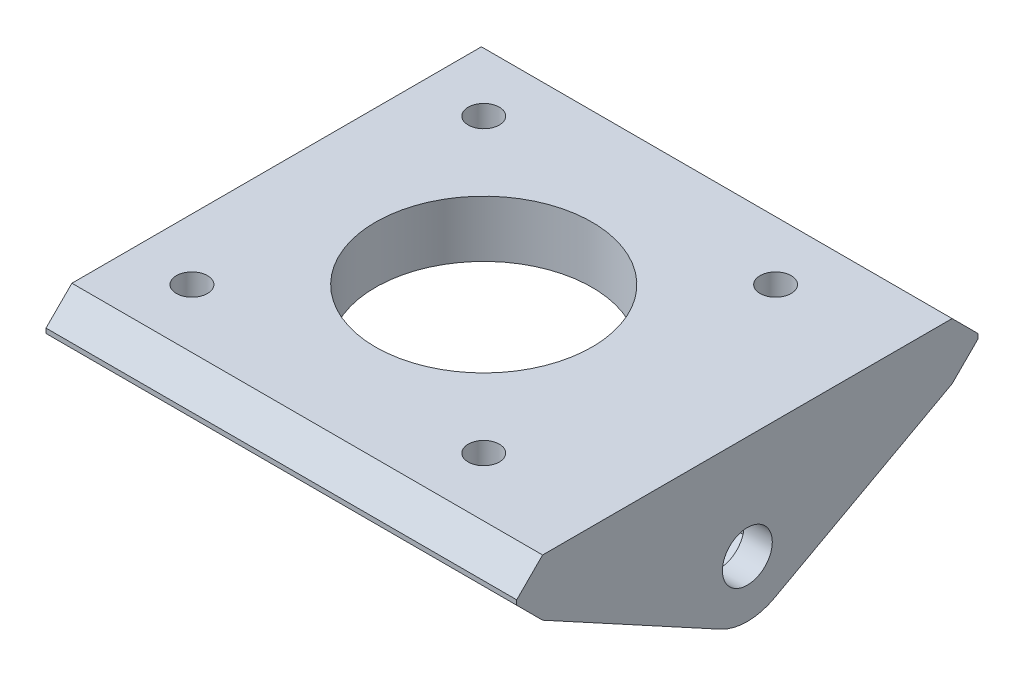
SolidWorks part; units mm, degrees
ref_plane "Front Plane" through (0, 0, 0) normal (0, 0, 1) x (1, 0, 0)
ref_plane "Top Plane" through (0, 0, 0) normal (0, 1, 0) x (1, 0, 0)
ref_plane "Right Plane" through (0, 0, 0) normal (1, 0, 0) x (0, 0, -1)
sketch "Sketch1" plane through (0, 0, 0) normal (0, 1, 0) x (1, 0, 0)
  line L1 (-22, -24.5) -> (22, -24.5)
  line L2 (-22, -24.5) -> (-22, 24.5)
  line L3 (-22, 24.5) -> (22, 24.5)
  line L4 (22, -24.5) -> (22, 24.5)
  line L5 (-22, -24.5) -> (22, 24.5) construction
  line L6 (-22, 24.5) -> (22, -24.5) construction
  line L11 (-15.5, -15.5) -> (15.5, 15.5) construction
  line L12 (-15.5, 15.5) -> (15.5, -15.5) construction
  line L13 (-15.5, 15.5) -> (15.5, 15.5) construction
  line L14 (-15.5, 15.5) -> (-15.5, -15.5) construction
  line L15 (-15.5, -15.5) -> (15.5, -15.5) construction
  line L16 (15.5, 15.5) -> (15.5, -15.5) construction
  line L17 (-15.5, 15.5) -> (15.5, -15.5) construction
  line L18 (-15.5, -15.5) -> (15.5, 15.5) construction
  circle A0 centre (0, 0) radius 11.5
  circle A1 centre (15.5, 15.5) radius 1.65
  circle A2 centre (15.5, -15.5) radius 1.65
  circle A3 centre (-15.5, -15.5) radius 1.65
  circle A4 centre (-15.5, 15.5) radius 1.65
  point P0 (0, 0)
  point P8 (-15.414, -15.414)
  point P10 (0, 0)
  point P11 (0, 0)
  point P13 (0, 0)
  point P15 (0, 0)
  point P19 (0, 0)
  point P20 (14.9848, 14.8863)
  dimension "D2" = 23
  dimension "D3" = 31
  dimension "D4" = 3.3
  dimension "D1" = 44
  dimension "D6" = 49
extrude "Boss-Extrude1" add sketch "Sketch1" along normal blind 6
chamfer "Chamfer1" distance 2.75 angle 45 8 edges at (22, 0, 0) (22, 6, 0) (-22, 0, 0) (-22, 6, 0) (0, 0, -24.5) (0, 6, -24.5) (0, 6, 24.5) (0, 0, 24.5)
sketch "Sketch2" plane through (22, 0, 0) normal (1, 0, 0) x (0, 0, -1)
  line L0 (0, -5) -> (0, 0) construction
  line L1 (-21.75, 6) -> (21.75, 6)
  line L2 (-21.75, 6) -> (-21.75, 0)
  line L4 (21.75, 6) -> (21.75, 0)
  line L5 (0, -9.9075) -> (4.25, -7.4537)
  line L6 (4.25, -7.4537) -> (4.25, -2.5463)
  line L7 (4.25, -2.5463) -> (0, -0.0925)
  line L8 (0, -0.0925) -> (-4.25, -2.5463)
  line L9 (-4.25, -2.5463) -> (-4.25, -7.4537)
  line L10 (-4.25, -7.4537) -> (0, -9.9075)
  line L11 (21.75, 0) -> (2.8668, -10.2708)
  line L12 (-21.75, 0) -> (-2.8668, -10.2708)
  circle A0 centre (0, -5) radius 4.25 construction
  arc A1 (-2.8668, -10.2708) -> (2.8668, -10.2708) centre (0, -5) ccw
  dimension "D3" = 6
  dimension "D1" = 8.5
  dimension "D2" = 5
extrude "Boss-Extrude2" add sketch "Sketch2" along normal blind 3
sketch "Sketch3" plane through (25, 0, 0) normal (1, 0, 0) x (0, 0, -1)
  line L0 (-21.75, 6) -> (21.75, 6)
  line L1 (21.75, 6) -> (21.75, 0)
  line L2 (21.75, 0) -> (2.8668, -10.2708)
  line L3 (-21.75, 0) -> (-2.8668, -10.2708)
  arc A0 (-2.8668, -10.2708) -> (2.8668, -10.2708) centre (0, -5) ccw
  circle A1 centre (0, -5) radius 2.65
  line M6 (-21.75, 6) -> (-21.75, 0)
  line M7 (-21.75, 0) -> (-2.8668, -10.2708)
  arc M8 (-2.8668, -10.2708) -> (2.8668, -10.2708) centre (0, -5) ccw
  line M9 (2.8668, -10.2708) -> (21.75, 0)
  line M10 (21.75, 0) -> (21.75, 6)
  line M11 (21.75, 6) -> (-21.75, 6)
  line M12 (4.25, -7.4537) -> (0, -9.9075)
  line M13 (0, -9.9075) -> (-4.25, -7.4537)
  line M14 (-4.25, -7.4537) -> (-4.25, -2.5463)
  line M15 (-4.25, -2.5463) -> (0, -0.0925)
  line M16 (0, -0.0925) -> (4.25, -2.5463)
  line M17 (4.25, -2.5463) -> (4.25, -7.4537)
  dimension "D1" = 5.3
extrude "Boss-Extrude3" add sketch "Sketch3" along normal blind 3 contours M11 M6 M7 M8 M9 M10 M17 M12 M13 M14 M15 M16 | A1 M12 M17 M16 M15 M14 M13
sketch "Sketch4" plane through (22, 0, 0) normal (1, 0, 0) x (0, 0, -1)
  line L4 (-21.75, 0) -> (-21.75, 6)
  line L5 (-21.75, 6) -> (-24.5, 3.25)
  line L6 (-24.5, 3.25) -> (-24.5, 2.75)
  line L7 (-24.5, 2.75) -> (-21.75, 0)
  line L8 (-21.75, 0) -> (-21.75, 6)
  line L9 (-21.75, 6) -> (-24.5, 3.25)
  line L10 (-24.5, 3.25) -> (-24.5, 2.75)
  line L11 (-24.5, 2.75) -> (-21.75, 0)
  line L12 (21.75, 6) -> (21.75, 0)
  line L13 (21.75, 0) -> (24.5, 2.75)
  line L14 (24.5, 2.75) -> (24.5, 3.25)
  line L15 (24.5, 3.25) -> (21.75, 6)
  line L16 (21.75, 6) -> (21.75, 0)
  line L17 (21.75, 0) -> (24.5, 2.75)
  line L18 (24.5, 2.75) -> (24.5, 3.25)
  line L19 (24.5, 3.25) -> (21.75, 6)
  dimension "D1" = 0
  dimension "D2" = 0
extrude "Boss-Extrude4" add sketch "Sketch4" along normal up to surface (6 mm away) up to face at (28, -1.5451, 0)
fillet "Fillet1" radius 2 2 edges at (0, 0, 21.75) (0, 0, -21.75)
